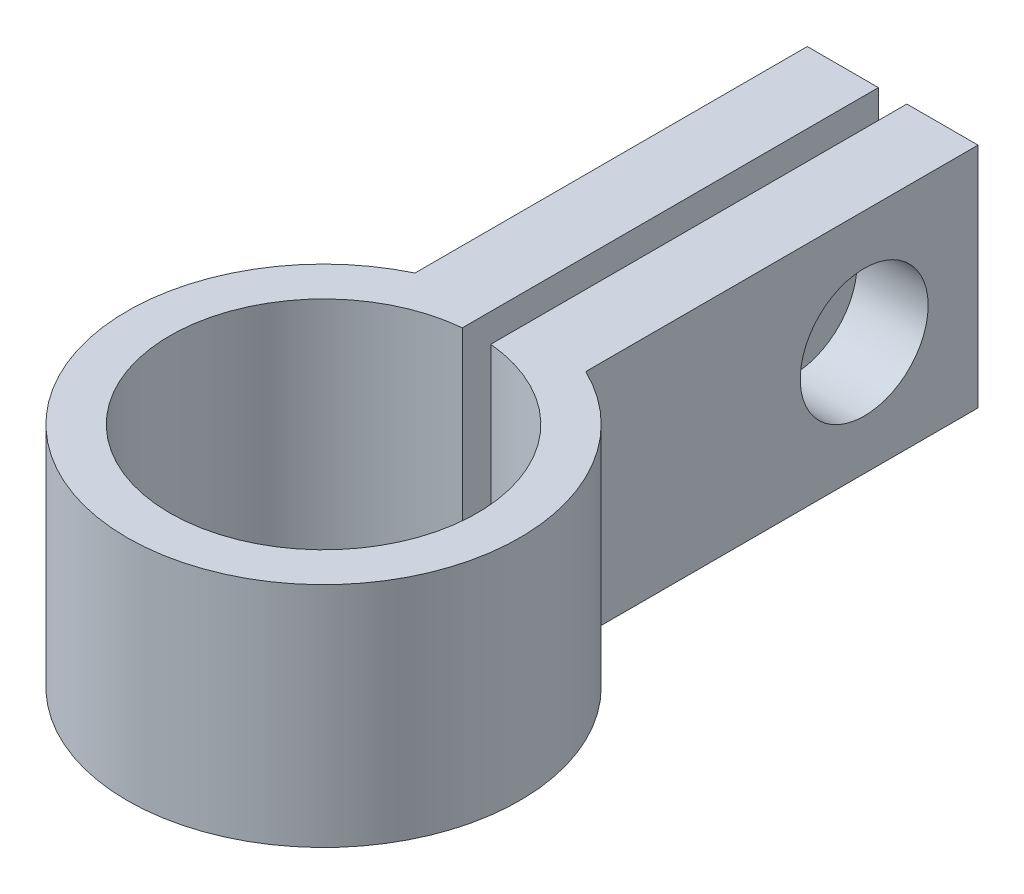
SolidWorks part; units mm, degrees
ref_plane "Front Plane" through (0, 0, 0) normal (0, 0, 1) x (1, 0, 0)
ref_plane "Top Plane" through (0, 0, 0) normal (0, 1, 0) x (1, 0, 0)
ref_plane "Right Plane" through (0, 0, 0) normal (1, 0, 0) x (0, 0, -1)
sketch "Sketch1" plane through (0, 0, 0) normal (0, 1, 0) x (1, 0, 0)
  line L1 (3, -6.2) -> (-3, -6.2)
  line L2 (3, -6.2) -> (3, 20)
  line L3 (3, 20) -> (-3, 20)
  line L4 (-3, -6.2) -> (-3, 20)
  line L5 (3, -6.2) -> (-3, 20) construction
  line L6 (3, 20) -> (-3, -6.2) construction
  line L7 (0.5, -6.2) -> (-0.5, -6.2)
  line L8 (0.5, -6.2) -> (0.5, 20)
  line L9 (0.5, 20) -> (-0.5, 20)
  line L10 (-0.5, -6.2) -> (-0.5, 20)
  line L11 (0.5, -6.2) -> (-0.5, 20) construction
  line L12 (0.5, 20) -> (-0.5, -6.2) construction
  circle A0 centre (0, 0) radius 5.4
  circle A1 centre (0, 0) radius 6.9
  point P4 (0, 6.9)
  point P9 (0, 6.9)
  dimension "D1" = 10.8
  dimension "D2" = 1.5
  dimension "D3" = 6
  dimension "D4" = 20
  dimension "D5" = 1
extrude "Boss-Extrude1" add sketch "Sketch1" along normal blind 8 contours L4 A1 L2 A0 | L10 A1 L4 A0 | A1 L10 L3 L4 | A1 L2 L3 L8 | L2 A1 L8 A0 | A0 L4 L1 L10 | A0 L8 L1 L2 | A0 L10 L1 L8
sketch "Sketch2" plane through (3, 0, 0) normal (1, 0, 0) x (0, 0, -1)
  line L1 (20, 8) -> (20, 0) construction
  line L2 (20, 8) -> (20, 0) construction
  point P0 (16, 4)
  point P6 (20, 4)
  dimension "D1" = 4
  dimension "D2" = 0
hole_wizard "#8 Clearance Hole1" positions "Sketch3" profile "Sketch4" hole size "#8" standard "ANSI Inch" end condition through all
sketch "Sketch3" plane through (3, 0, 0) normal (1, 0, 0) x (0, 0, -1)
  point P0 (16, 4)
sketch "Sketch4" plane through (3, 4, -16) normal (0, 1, 0) x (0, 0, -1)
  line L0 (0, 0) -> (0, 9.9)
  line L1 (0, 9.9) -> (2.2479, 9.9)
  line L2 (2.2479, 9.9) -> (2.2479, 0)
  line L5 (2.2479, 0) -> (0, 0)
  line L11 (0, -6.35) -> (0, 107.95) construction
  dimension "Thru Hole Dia." = 4.4958
  dimension "Thru Hole Depth" = 9.9
